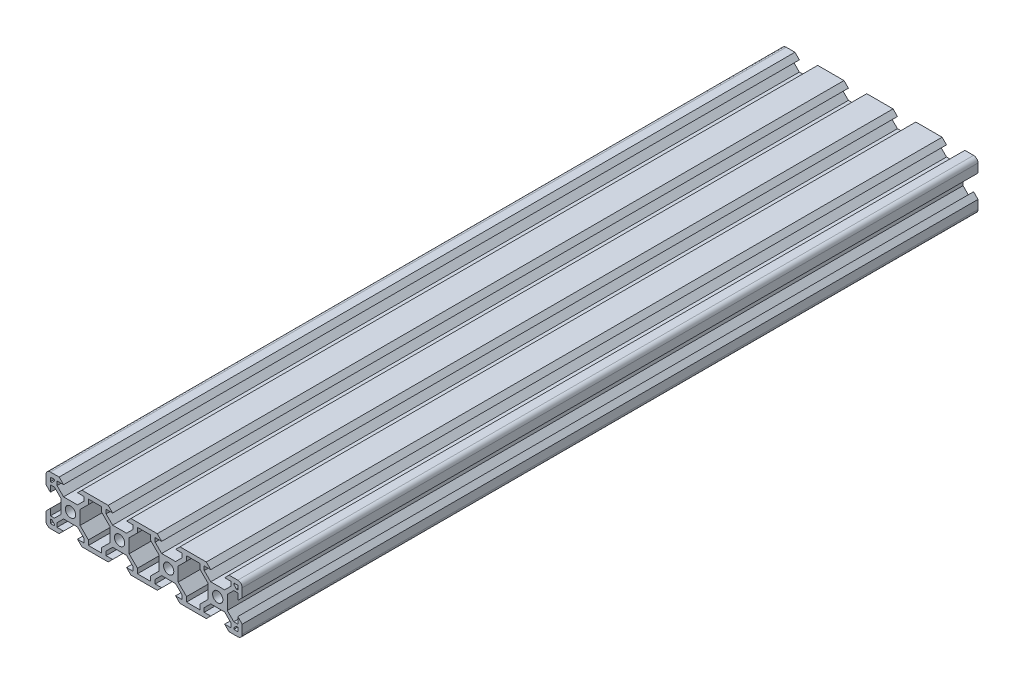
SolidWorks part; units mm, degrees
material "5052-H38, Barre (SS)"
ref_plane "Plan de face" through (0, 0, 0) normal (0, 0, 1) x (1, 0, 0)
ref_plane "Plan de dessus" through (0, 0, 0) normal (0, 1, 0) x (1, 0, 0)
ref_plane "Plan de droite" through (0, 0, 0) normal (1, 0, 0) x (0, 0, -1)
sketch "Esquisse1" plane through (0, 0, 0) normal (0, 0, 1) x (1, 0, 0)
  line L0 (0, 0) -> (0, 10) construction
  line L1 (0, 0) -> (-40, 0) construction
  line L2 (-40, 10) -> (-30, 0) construction
  line L3 (-30, 0) -> (-20, 10) construction
  line L4 (-20, 10) -> (-10, 0) construction
  line L5 (-10, 0) -> (0, 10) construction
  line L6 (-10, 0) -> (-10, 10) construction
  line L7 (-20, 10) -> (-20, 0) construction
  line L8 (-40, 0) -> (-40, 10) construction
  line L9 (-38.2, 10) -> (-34.64, 10)
  line L10 (-34.64, 10) -> (-32.84, 8.2)
  line L11 (-32.84, 8.2) -> (-35.4993, 8.2)
  line L12 (-35.4993, 8.2) -> (-35.4993, 6.56)
  line L13 (-35.4993, 6.56) -> (-32.84, 3.9007)
  line L14 (-32.84, 3.9007) -> (-27.16, 3.9007)
  line L15 (-30, 0) -> (-30, 10) construction
  line L16 (-33.9007, 2.84) -> (-33.9007, 0)
  line L17 (-36.56, 5.4993) -> (-33.9007, 2.84)
  line L18 (-38.2, 5.4993) -> (-36.56, 5.4993)
  line L19 (-38.2, 2.84) -> (-38.2, 5.4993)
  line L20 (-40, 4.64) -> (-38.2, 2.84)
  line L21 (-40, 8.2) -> (-40, 4.64)
  line L22 (-38.2, 8.2) -> (-38.2, 6.5693)
  line L23 (-38.2, 6.5693) -> (-37.63, 6.5693)
  line L24 (-37.63, 6.5693) -> (-36.5693, 7.63)
  line L25 (-36.5693, 7.63) -> (-36.5693, 8.2)
  line L26 (-36.5693, 8.2) -> (-38.2, 8.2)
  line L27 (-17.3, 6.2393) -> (-17.3, 8.2)
  line L28 (-13.9007, 2.84) -> (-17.3, 6.2393)
  line L29 (-13.9007, -2.84) -> (-13.9007, 2.84)
  line L30 (-14.64, 10) -> (-12.84, 8.2)
  line L31 (-12.84, 8.2) -> (-15.4993, 8.2)
  line L32 (-15.4993, 8.2) -> (-15.4993, 6.56)
  line L33 (-15.4993, 6.56) -> (-12.84, 3.9007)
  line L34 (-12.84, 3.9007) -> (-7.16, 3.9007)
  line L35 (-5.36, 10) -> (-7.16, 8.2)
  line L36 (-7.16, 8.2) -> (-4.5007, 8.2)
  line L37 (-4.5007, 8.2) -> (-4.5007, 6.56)
  line L38 (-4.5007, 6.56) -> (-7.16, 3.9007)
  line L39 (-5.36, 10) -> (5.36, 10)
  line L40 (-6.0993, -2.84) -> (-6.0993, 2.84)
  line L41 (-6.0993, 2.84) -> (-2.7, 6.2393)
  line L42 (-2.7, 6.2393) -> (-2.7, 8.2)
  line L43 (-2.7, 8.2) -> (2.7, 8.2)
  line L44 (-25.36, 10) -> (-27.16, 8.2)
  line L45 (-7.16, 3.9007) -> (-6.0993, 2.84) construction
  line L46 (-36.5693, -7.63) -> (-36.5693, -8.2)
  line L47 (-37.63, -6.5693) -> (-36.5693, -7.63)
  line L48 (-38.2, -6.5693) -> (-37.63, -6.5693)
  line L49 (-38.2, -8.2) -> (-38.2, -6.5693)
  line L50 (-27.16, 8.2) -> (-24.5007, 8.2)
  line L51 (-24.5007, 8.2) -> (-24.5007, 6.56)
  line L52 (-24.5007, 6.56) -> (-27.16, 3.9007)
  line L53 (-25.36, 10) -> (-14.64, 10)
  line L54 (-26.0993, -2.84) -> (-26.0993, 2.84)
  line L55 (-26.0993, 2.84) -> (-22.7, 6.2393)
  line L56 (-22.7, 6.2393) -> (-22.7, 8.2)
  line L57 (-22.7, 8.2) -> (-17.3, 8.2)
  line L58 (-27.16, 3.9007) -> (-26.0993, 2.84) construction
  line L59 (-26.0993, 2.84) -> (-26.0962, 2.8177) construction
  line L60 (-36.5693, -8.2) -> (-38.2, -8.2)
  line L61 (-26.0993, -2.84) -> (-22.7, -6.2393)
  line L62 (-22.7, -6.2393) -> (-22.7, -8.2)
  line L63 (-22.7, -8.2) -> (-17.3, -8.2)
  line L64 (-17.3, -6.2393) -> (-17.3, -8.2)
  line L65 (-13.9007, -2.84) -> (-17.3, -6.2393)
  line L66 (-2.7, -8.2) -> (2.7, -8.2)
  line L67 (-2.7, -6.2393) -> (-2.7, -8.2)
  line L68 (-6.0993, -2.84) -> (-2.7, -6.2393)
  line L69 (-5.36, -10) -> (5.36, -10)
  line L70 (-5.36, -10) -> (-7.16, -8.2)
  line L71 (-7.16, -8.2) -> (-4.5007, -8.2)
  line L72 (-4.5007, -8.2) -> (-4.5007, -6.56)
  line L73 (-4.5007, -6.56) -> (-7.16, -3.9007)
  line L74 (-12.84, -3.9007) -> (-7.16, -3.9007)
  line L75 (-15.4993, -6.56) -> (-12.84, -3.9007)
  line L76 (-15.4993, -8.2) -> (-15.4993, -6.56)
  line L77 (-12.84, -8.2) -> (-15.4993, -8.2)
  line L78 (-14.64, -10) -> (-12.84, -8.2)
  line L79 (-25.36, -10) -> (-14.64, -10)
  line L80 (-25.36, -10) -> (-27.16, -8.2)
  line L81 (-27.16, -8.2) -> (-24.5007, -8.2)
  line L82 (-24.5007, -8.2) -> (-24.5007, -6.56)
  line L83 (-24.5007, -6.56) -> (-27.16, -3.9007)
  line L84 (-32.84, -3.9007) -> (-27.16, -3.9007)
  line L85 (-35.4993, -6.56) -> (-32.84, -3.9007)
  line L86 (-35.4993, -8.2) -> (-35.4993, -6.56)
  line L87 (-32.84, -8.2) -> (-35.4993, -8.2)
  line L88 (-34.64, -10) -> (-32.84, -8.2)
  line L89 (-38.2, -10) -> (-34.64, -10)
  line L90 (-40, -8.2) -> (-40, -4.64)
  line L91 (-40, -4.64) -> (-38.2, -2.84)
  line L92 (-38.2, -2.84) -> (-38.2, -5.4993)
  line L93 (-38.2, -5.4993) -> (-36.56, -5.4993)
  line L94 (-36.56, -5.4993) -> (-33.9007, -2.84)
  line L95 (-33.9007, -2.84) -> (-33.9007, 0)
  line L96 (36.5693, 8.2) -> (38.2, 8.2)
  line L97 (36.5693, 7.63) -> (36.5693, 8.2)
  line L98 (37.63, 6.5693) -> (36.5693, 7.63)
  line L99 (38.2, 6.5693) -> (37.63, 6.5693)
  line L100 (38.2, 8.2) -> (38.2, 6.5693)
  line L101 (36.5693, -8.2) -> (38.2, -8.2)
  line L102 (36.5693, -7.63) -> (36.5693, -8.2)
  line L103 (37.63, -6.5693) -> (36.5693, -7.63)
  line L104 (38.2, -6.5693) -> (37.63, -6.5693)
  line L105 (38.2, -8.2) -> (38.2, -6.5693)
  line L106 (13.9007, -2.84) -> (17.3, -6.2393)
  line L107 (17.3, -6.2393) -> (17.3, -8.2)
  line L108 (22.7, -8.2) -> (17.3, -8.2)
  line L109 (22.7, -6.2393) -> (22.7, -8.2)
  line L110 (26.0993, -2.84) -> (22.7, -6.2393)
  line L111 (26.0993, -2.84) -> (26.0993, 2.84)
  line L112 (26.0993, 2.84) -> (22.7, 6.2393)
  line L113 (22.7, 6.2393) -> (22.7, 8.2)
  line L114 (22.7, 8.2) -> (17.3, 8.2)
  line L115 (17.3, 6.2393) -> (17.3, 8.2)
  line L116 (13.9007, 2.84) -> (17.3, 6.2393)
  line L117 (13.9007, -2.84) -> (13.9007, 2.84)
  line L118 (2.7, -6.2393) -> (2.7, -8.2)
  line L119 (6.0993, -2.84) -> (2.7, -6.2393)
  line L120 (6.0993, -2.84) -> (6.0993, 2.84)
  line L121 (6.0993, 2.84) -> (2.7, 6.2393)
  line L122 (2.7, 6.2393) -> (2.7, 8.2)
  line L123 (5.36, -10) -> (7.16, -8.2)
  line L124 (7.16, -8.2) -> (4.5007, -8.2)
  line L125 (4.5007, -8.2) -> (4.5007, -6.56)
  line L126 (4.5007, -6.56) -> (7.16, -3.9007)
  line L127 (12.84, -3.9007) -> (7.16, -3.9007)
  line L128 (15.4993, -6.56) -> (12.84, -3.9007)
  line L129 (15.4993, -8.2) -> (15.4993, -6.56)
  line L130 (12.84, -8.2) -> (15.4993, -8.2)
  line L131 (14.64, -10) -> (12.84, -8.2)
  line L132 (25.36, -10) -> (14.64, -10)
  line L133 (25.36, -10) -> (27.16, -8.2)
  line L134 (27.16, -8.2) -> (24.5007, -8.2)
  line L135 (24.5007, -8.2) -> (24.5007, -6.56)
  line L136 (24.5007, -6.56) -> (27.16, -3.9007)
  line L137 (32.84, -3.9007) -> (27.16, -3.9007)
  line L138 (35.4993, -6.56) -> (32.84, -3.9007)
  line L139 (35.4993, -8.2) -> (35.4993, -6.56)
  line L140 (32.84, -8.2) -> (35.4993, -8.2)
  line L141 (34.64, -10) -> (32.84, -8.2)
  line L142 (38.2, -10) -> (34.64, -10)
  line L143 (40, -8.2) -> (40, -4.64)
  line L144 (40, -4.64) -> (38.2, -2.84)
  line L145 (38.2, -2.84) -> (38.2, -5.4993)
  line L146 (38.2, -5.4993) -> (36.56, -5.4993)
  line L147 (36.56, -5.4993) -> (33.9007, -2.84)
  line L148 (33.9007, -2.84) -> (33.9007, 0)
  line L149 (33.9007, 2.84) -> (33.9007, 0)
  line L150 (36.56, 5.4993) -> (33.9007, 2.84)
  line L151 (38.2, 5.4993) -> (36.56, 5.4993)
  line L152 (38.2, 2.84) -> (38.2, 5.4993)
  line L153 (40, 4.64) -> (38.2, 2.84)
  line L154 (40, 8.2) -> (40, 4.64)
  line L155 (38.2, 10) -> (34.64, 10)
  line L156 (34.64, 10) -> (32.84, 8.2)
  line L157 (32.84, 8.2) -> (35.4993, 8.2)
  line L158 (35.4993, 8.2) -> (35.4993, 6.56)
  line L159 (35.4993, 6.56) -> (32.84, 3.9007)
  line L160 (32.84, 3.9007) -> (27.16, 3.9007)
  line L161 (24.5007, 6.56) -> (27.16, 3.9007)
  line L162 (24.5007, 8.2) -> (24.5007, 6.56)
  line L163 (27.16, 8.2) -> (24.5007, 8.2)
  line L164 (25.36, 10) -> (27.16, 8.2)
  line L165 (25.36, 10) -> (14.64, 10)
  line L166 (14.64, 10) -> (12.84, 8.2)
  line L167 (12.84, 8.2) -> (15.4993, 8.2)
  line L168 (15.4993, 8.2) -> (15.4993, 6.56)
  line L169 (15.4993, 6.56) -> (12.84, 3.9007)
  line L170 (12.84, 3.9007) -> (7.16, 3.9007)
  line L171 (4.5007, 6.56) -> (7.16, 3.9007)
  line L172 (4.5007, 8.2) -> (4.5007, 6.56)
  line L173 (7.16, 8.2) -> (4.5007, 8.2)
  line L174 (5.36, 10) -> (7.16, 8.2)
  circle A0 centre (-30, 0) radius 2.1
  circle A1 centre (-10, 0) radius 2.1
  arc A2 (-38.2, 10) -> (-40, 8.2) centre (-38.2, 8.2) ccw
  arc A3 (-38.2, -10) -> (-40, -8.2) centre (-38.2, -8.2) cw
  circle A4 centre (30, 0) radius 2.1
  circle A5 centre (10, 0) radius 2.1
  arc A6 (38.2, -10) -> (40, -8.2) centre (38.2, -8.2) ccw
  arc A7 (38.2, 10) -> (40, 8.2) centre (38.2, 8.2) cw
  point P21 (-37.0997, 7.0997)
  point P36 (-20, 8.2)
  point P47 (-10, 3.9007)
  point P54 (-6.6297, 3.3703)
  point P61 (-30, 3.9007)
  point P71 (-26.0993, 0)
  point P76 (-13.9007, 0)
  point P80 (-6.0993, 0)
  point P135 (0, -8.2)
  point P140 (0, 8.2)
  point P141 (0, -10)
  dimension "D3" = 4.2
  dimension "D4" = 4.2
  dimension "D1" = 40
  dimension "D2" = 10
  dimension "D5" = 5.68
  dimension "D6" = 1.5
  dimension "D7" = 1.64
  dimension "D8" = 1.8
  dimension "D9" = 1.07
  dimension "D11" = 5.4
extrude "Boss.-Extru.1" add sketch "Esquisse1" along normal mid plane 300
